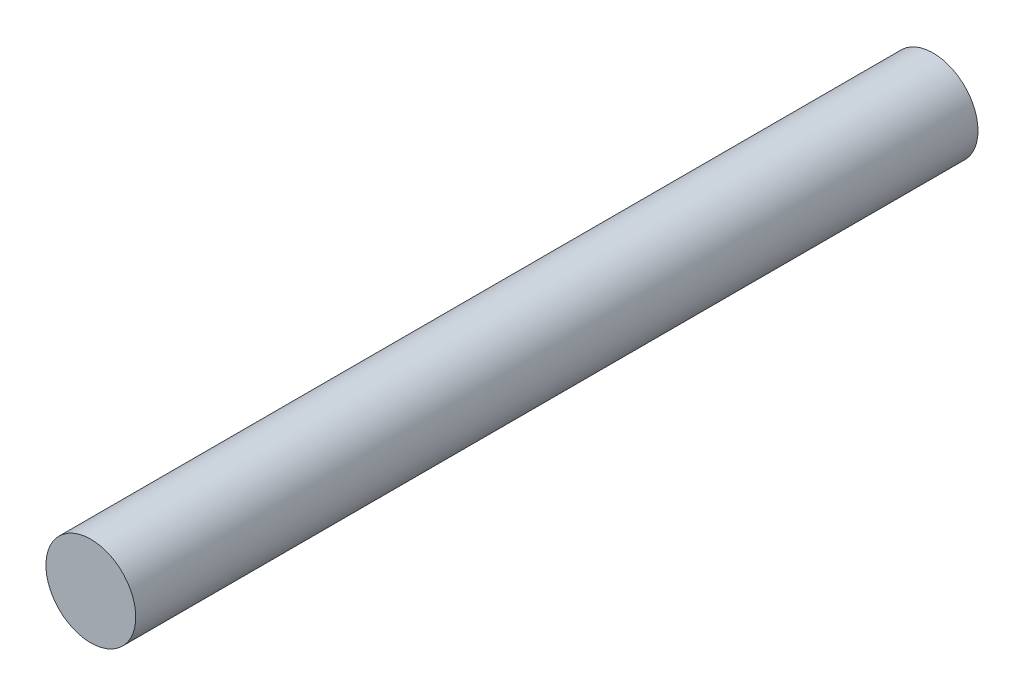
SolidWorks part; units mm, degrees
ref_plane "Front Plane" through (0, 0, 0) normal (0, 0, 1) x (1, 0, 0)
ref_plane "Top Plane" through (0, 0, 0) normal (0, 1, 0) x (1, 0, 0)
ref_plane "Right Plane" through (0, 0, 0) normal (1, 0, 0) x (0, 0, -1)
sketch "Sketch1" plane through (0, 0, 0) normal (0, 0, 1) x (1, 0, 0)
  circle A0 centre (0, 0) radius 0.4
  dimension "D1" = 0.8
extrude "Boss-Extrude1" add sketch "Sketch1" along normal blind 7.5
